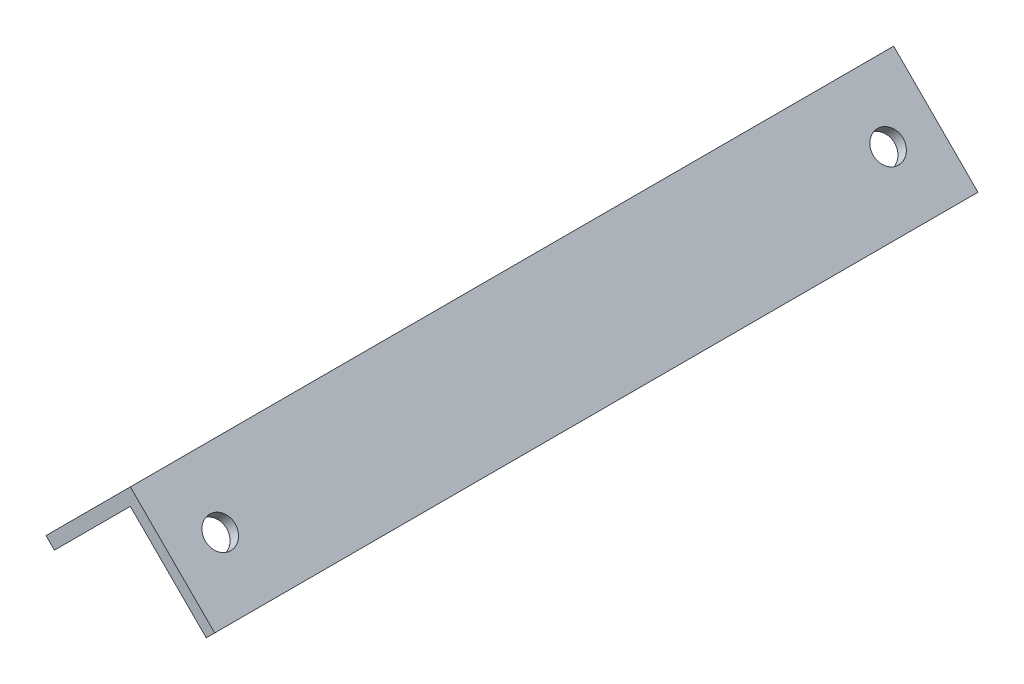
SolidWorks part; units mm, degrees
material "1060 Alloy"
ref_plane "Front Plane" through (0, 0, 0) normal (0, 0, 1) x (1, 0, 0)
ref_plane "Top Plane" through (0, 0, 0) normal (0, 1, 0) x (1, 0, 0)
ref_plane "Right Plane" through (0, 0, 0) normal (1, 0, 0) x (0, 0, -1)
sketch "Sketch1" plane through (0, 0, 0) normal (0, 0, 1) x (1, 0, 0)
  line L0 (0, 0) -> (22.4506, 22.4506)
  line L1 (22.4506, 22.4506) -> (44.9013, 0)
  line L2 (44.9013, 0) -> (42.6562, -2.2451)
  line L3 (42.6562, -2.2451) -> (22.4506, 17.9605)
  line L4 (22.4506, 17.9605) -> (2.2451, -2.2451)
  line L5 (2.2451, -2.2451) -> (0, 0)
  dimension "D1" = 31.75
  dimension "D2" = 3.175
extrude "Boss-Extrude1" add sketch "Sketch1" along normal blind 203.2
sketch "Sketch4" plane through (0, 0, 0) normal (-0.7071, 0.7071, 0) x (0, 0, 1)
  line L0 (31.75, 15.875) -> (101.6, 15.875) construction
  line L1 (101.6, 15.875) -> (171.45, 15.875) construction
  line L2 (101.6, 31.75) -> (101.6, 15.875) construction
  line L3 (203.2, 31.75) -> (0, 31.75) construction
  line L4 (101.6, 15.875) -> (101.6, 0) construction
  line L5 (203.2, 0) -> (0, 0) construction
  line L6 (0, 31.75) -> (0, 0) construction
  circle A0 centre (31.75, 15.875) radius 3.9751
  circle A1 centre (171.45, 15.875) radius 3.9751
  point P6 (101.6, 0)
  dimension "D1" = 7.9502
  dimension "D2" = 31.75
extrude "Cut-Extrude3" cut sketch "Sketch4" against normal through all
ref_plane "Plan1" through (0, -2.2451, 0) normal (0, 1, 0) x (-1, 0, 0)
sketch "Esquisse1" plane through (22.4506, 22.4506, 0) normal (0.7071, 0.7071, 0) x (-0.7071, 0.7071, 0)
  line L1 (-31.75, 203.2) -> (-31.75, 0) construction
  line L2 (0, 12.7) -> (-31.75, 12.7) construction
  line L3 (0, 203.2) -> (0, 0) construction
  line L5 (-31.75, 0) -> (0, 0) construction
  circle A0 centre (-15.875, 12.7) radius 3.9751
  point P8 (-15.875, 12.7)
  dimension "D1" = 12.7
  dimension "D3" = 7.9502
  dimension "D2" = 15.875
extrude "Enlèv. mat.-Extru.1" cut sketch "Esquisse1" against normal through all
ref_plane "Plan2" through (0, 0, 101.6) normal (0, 0, 1) x (1, 0, 0)
mirror "Symétrie1" about plane through (0, 0, 101.6) normal (0, 0, 1) of "Enlèv. mat.-Extru.1"
ref_plane "Plan3" through (22.4506, 0, 0) normal (1, 0, 0) x (0, 0, -1)
